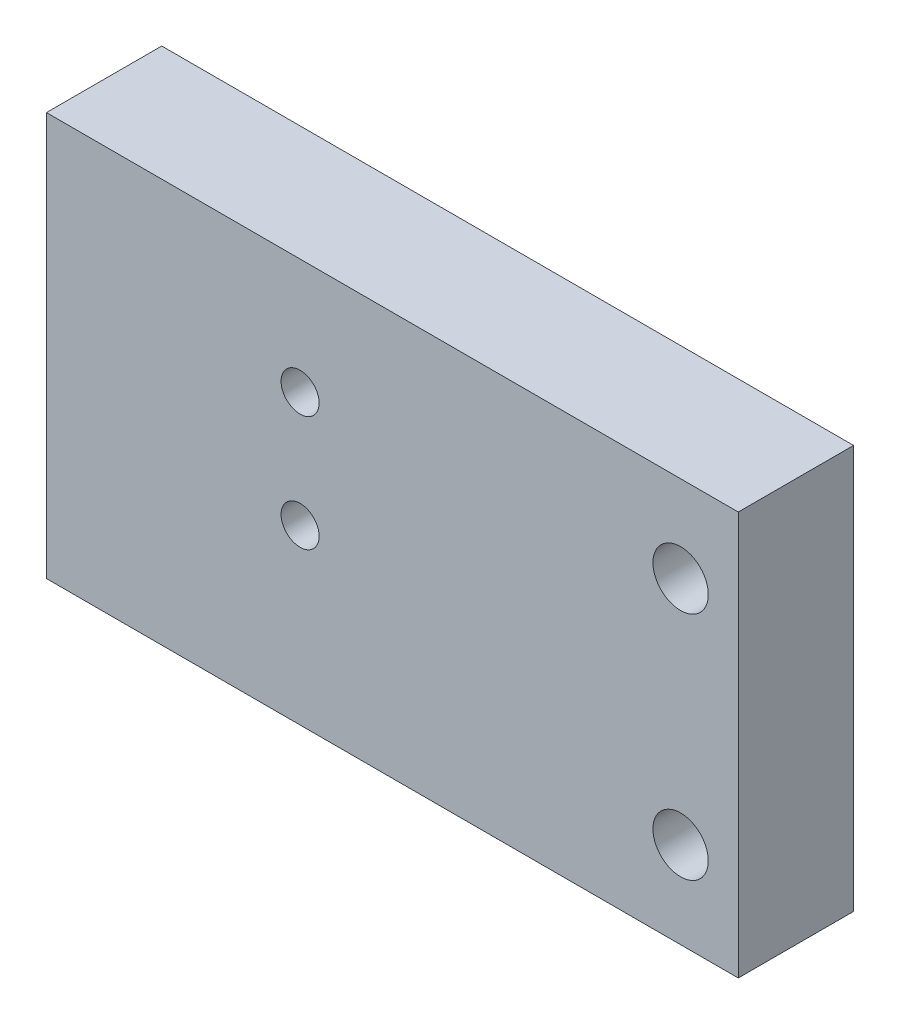
SolidWorks part; units mm, degrees
material "SKD11淬火HRC56-60"
ref_plane "前基準面" through (0, 0, 0) normal (0, 0, 1) x (1, 0, 0)
ref_plane "上基準面" through (0, 0, 0) normal (0, 1, 0) x (1, 0, 0)
ref_plane "右基準面" through (0, 0, 0) normal (1, 0, 0) x (0, 0, -1)
sketch "草图1" plane through (0, 0, 0) normal (0, 0, 1) x (1, 0, 0)
  line L1 (0, 0) -> (60, 0)
  line L2 (0, 0) -> (0, 35)
  line L3 (0, 35) -> (60, 35)
  line L4 (60, 0) -> (60, 35)
  dimension "D1" = 60
  dimension "D2" = 35
extrude "凸台-拉伸1" add sketch "草图1" along normal blind 10
hole_wizard "M4 六角凹头螺钉的柱形沉头孔1" positions "草图3" profile "草图2" counterbore size "M4" standard "ISO" end condition through all
sketch "草图3" plane through (0, 0, 0) normal (0, 0, -1) x (-1, 0, 0)
  line L0 (-60, 17.5) -> (-34.9182, 17.5) construction
  line L1 (-60, 0) -> (-60, 35) construction
  point P0 (-55, 7.5)
  point P1 (-55, 27.5)
  dimension "D1" = 20
  dimension "D2" = 5
sketch "草图2" plane through (55, 7.5, 0) normal (1, 0, 0) x (0, 1, 0)
  line L0 (0, 0) -> (0, 10)
  line L1 (0, 10) -> (2.4, 10)
  line L3 (2.4, 10) -> (2.4, 4)
  line L4 (2.4, 4) -> (4, 4)
  line L5 (4, 4) -> (4, 0)
  line L7 (4, 0) -> (0, 0)
  line L11 (0, -6.35) -> (0, 107.95) construction
  dimension "通孔孔直径" = 4.8
  dimension "通孔孔深度" = 10
  dimension "柱形沉头孔直径" = 8
  dimension "柱形沉头孔深度" = 4
hole_wizard "M4 螺纹孔1" positions "草图5" profile "草图4" tap size "M4" standard "ISO" end condition through all
sketch "草图5" plane through (0, 0, 0) normal (0, 0, -1) x (-1, 0, 0)
  line L0 (0, 0) -> (-60, 0) construction
  line L1 (-60, 0) -> (-60, 35) construction
  point P0 (-22, 25)
  point P1 (-22, 15)
  dimension "D1" = 10
  dimension "D2" = 15
  dimension "D3" = 38
sketch "草图4" plane through (22, 25, 0) normal (1, 0, 0) x (0, 1, 0)
  line L0 (0, 0) -> (0, 10)
  line L1 (0, 10) -> (1.65, 10)
  line L2 (1.65, 10) -> (1.65, 0)
  line L5 (1.65, 0) -> (0, 0)
  line L11 (0, -6.35) -> (0, 107.95) construction
  dimension "通孔螺纹孔钻头直径" = 3.3
  dimension "通孔螺纹孔钻头深度" = 10
cosmetic thread "孔螺蚊线1"
cosmetic thread "孔螺蚊线2"
